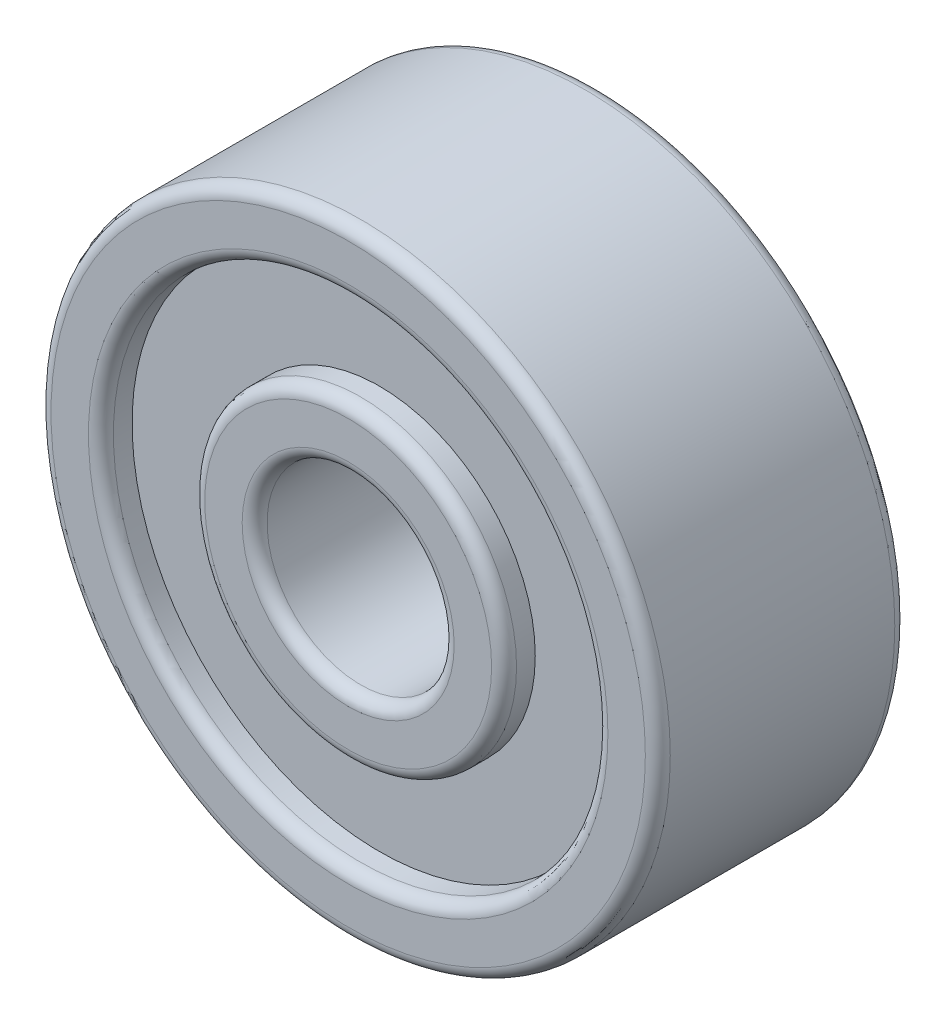
SolidWorks part; units mm, degrees
ref_plane "Alzado" through (0, 0, 0) normal (0, 0, 1) x (1, 0, 0)
ref_plane "Planta" through (0, 0, 0) normal (0, 1, 0) x (1, 0, 0)
ref_plane "Vista lateral" through (0, 0, 0) normal (1, 0, 0) x (0, 0, -1)
sketch "Croquis1" plane through (0, 0, 0) normal (0, 0, 1) x (1, 0, 0)
  circle A0 centre (0, 0) radius 4.965
  circle A1 centre (0, 0) radius 1.5
  dimension "D1" = 9.93
  dimension "D2" = 3
extrude "Saliente-Extruir1" add sketch "Croquis1" along normal blind 2
sketch "Croquis2" plane through (0, 0, 2) normal (0, 0, 1) x (1, 0, 0)
  circle A0 centre (0, 0) radius 2.5
  circle A1 centre (0, 0) radius 3.965
  circle A2 centre (0, 0) radius 4.965 construction
  circle A3 centre (0, 0) radius 1.5 construction
  dimension "D1" = 1
  dimension "D2" = 1
extrude "Cortar-Extruir1" cut sketch "Croquis2" against normal blind 0.5
fillet "Redondeo1" radius 0.2 4 edges at (1.5, 0, 2) (2.5, 0, 2) (3.965, 0, 2) (4.965, 0, 2)
mirror "Simetría3" about plane through (0, 0, 0) normal (0, 0, 1) of bodies 102
